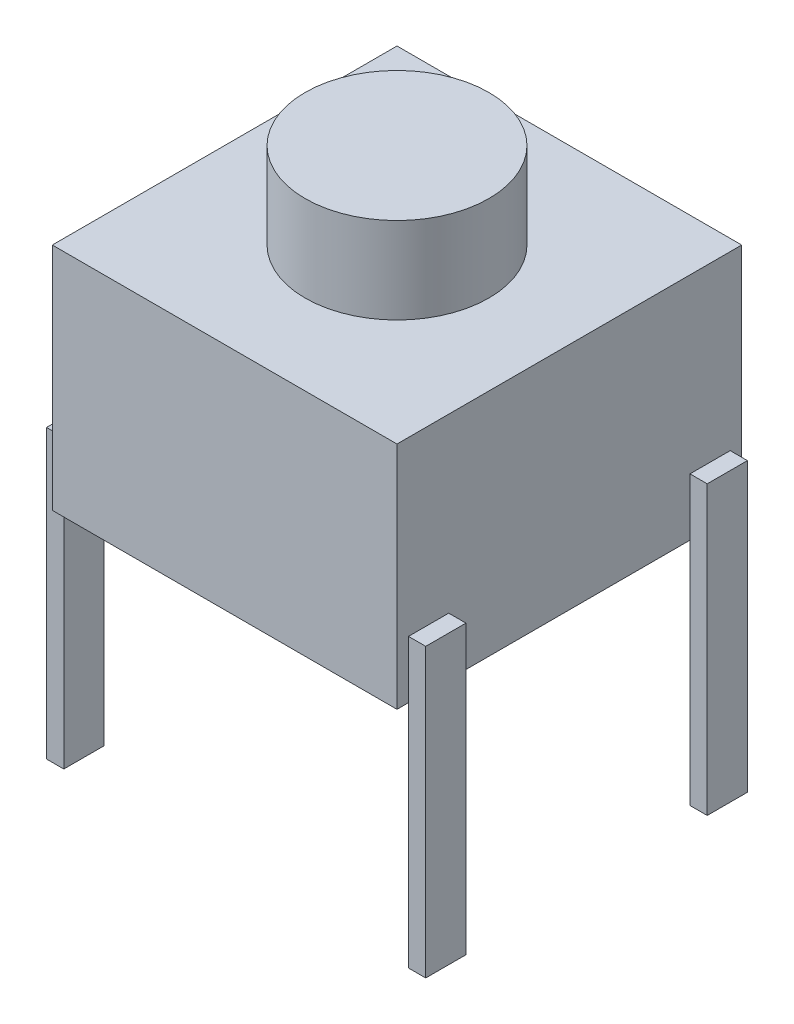
SolidWorks part; units mm, degrees
material "ABS"
ref_plane "Front Plane" through (0, 0, 0) normal (0, 0, 1) x (1, 0, 0)
ref_plane "Top Plane" through (0, 0, 0) normal (0, 1, 0) x (1, 0, 0)
ref_plane "Right Plane" through (0, 0, 0) normal (1, 0, 0) x (0, 0, -1)
sketch "Sketch1" plane through (0, 0, 0) normal (0, 1, 0) x (1, 0, 0)
  line L1 (0, 0) -> (6, 0)
  line L2 (0, 0) -> (0, 6)
  line L3 (0, 6) -> (6, 6)
  line L4 (6, 0) -> (6, 6)
  dimension "D1" = 6
  dimension "D2" = 6
extrude "Boss-Extrude1" add sketch "Sketch1" along normal blind 4
sketch "Sketch2" plane through (0, 4, 0) normal (0, 1, 0) x (1, 0, 0)
  line L0 (0, 6) -> (0, 0) construction
  line L1 (0, 0) -> (6, 0) construction
  circle A0 centre (3, 3) radius 1.6
  dimension "D3" = 3.2
  dimension "D1" = 3
  dimension "D2" = 3
extrude "Boss-Extrude2" add sketch "Sketch2" along normal blind 1.5
sketch "Sketch3" plane through (0, 0, 0) normal (-1, 0, 0) x (0, 0, 1)
  line L0 (-6, 0) -> (0, 0) construction
  line L1 (-0.2, 1) -> (-0.9, 1)
  line L2 (-0.2, 1) -> (-0.2, -4)
  line L3 (-0.2, -4) -> (-0.9, -4)
  line L4 (-0.9, 1) -> (-0.9, -4)
  line L5 (0, 4) -> (0, 0) construction
  dimension "D1" = 1
  dimension "D2" = 0.7
  dimension "D3" = 0.2
  dimension "D4" = 5
extrude "Boss-Extrude3" add sketch "Sketch3" along normal blind 0.3
pattern_linear "LPattern2" count 2 spacing 6.3 along (1, 0, 0) of "Boss-Extrude3"
pattern_linear "LPattern3" count 2 spacing 4.9 along (0, 0, -1) of "LPattern2", "Boss-Extrude3"
